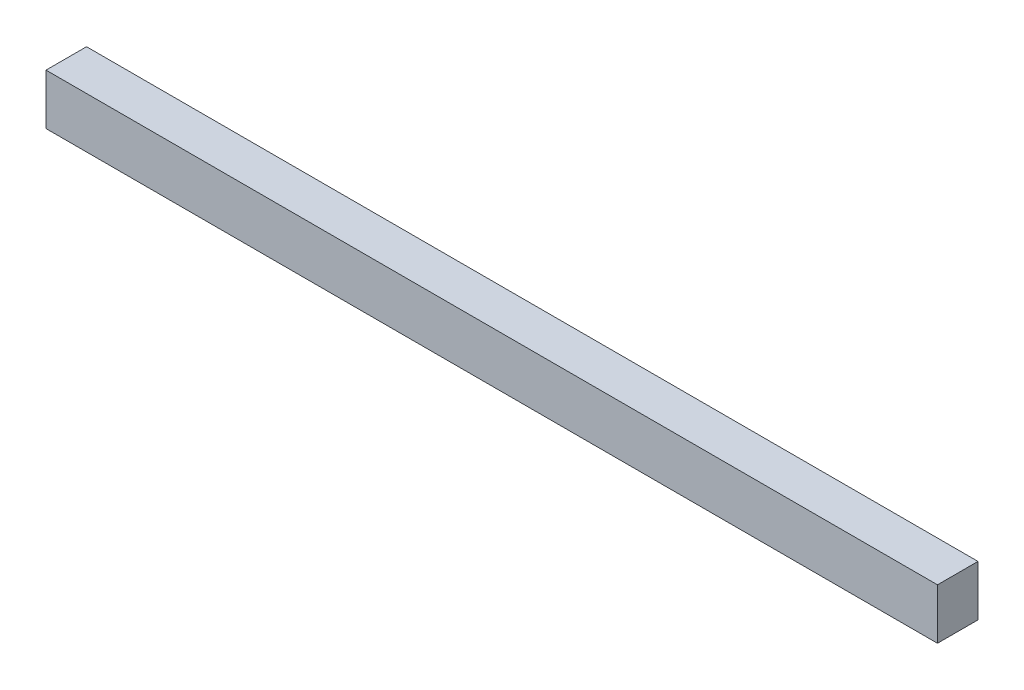
SolidWorks part; units mm, degrees
ref_plane "Front Plane" through (0, 0, 0) normal (0, 0, 1) x (1, 0, 0)
ref_plane "Top Plane" through (0, 0, 0) normal (0, 1, 0) x (1, 0, 0)
ref_plane "Right Plane" through (0, 0, 0) normal (1, 0, 0) x (0, 0, -1)
sketch "Sketch1" plane through (0, 0, 0) normal (0, 1, 0) x (1, 0, 0)
  line L1 (-220, 10) -> (220, 10)
  line L2 (-220, 10) -> (-220, -10)
  line L3 (-220, -10) -> (220, -10)
  line L4 (220, 10) -> (220, -10)
  line L5 (-220, 10) -> (220, -10) construction
  line L6 (-220, -10) -> (220, 10) construction
  point P0 (0, 0)
  dimension "D1" = 440
  dimension "D2" = 20
extrude "Boss-Extrude1" add sketch "Sketch1" along normal blind 25
hole_wizard "M5 Tapped Hole1" positions "Sketch4" profile "Sketch3" tap size "M5" standard "ISO"
sketch "Sketch4" plane through (0, 0, -10) normal (0, 0, -1) x (-1, 0, 0)
  line L0 (0, 0) -> (0, 25) construction
  line L1 (-220, 25) -> (220, 25) construction
  point P0 (0, 12.5)
  point P11 (0, 12.5)
  point P17 (60, 12.5)
  point P18 (120, 12.5)
  point P19 (180, 12.5)
  point P24 (-60, 12.5)
  point P25 (-120, 12.5)
  point P26 (-180, 12.5)
  dimension "D1" = 4
  dimension "D2" = 4
sketch "Sketch3" plane through (0, 12.5, -10) normal (1, 0, 0) x (0, 1, 0)
  line L0 (0, 0) -> (0, 16.2618)
  line L1 (0, 16.2618) -> (2.1, 15)
  line L2 (2.1, 15) -> (2.1, 0)
  line L5 (2.1, 0) -> (0, 0)
  line L10 (0, 16.2618) -> (-2.1, 15) construction
  line L11 (0, -6.35) -> (0, 107.95) construction
  dimension "Tap Drill Dia." = 4.2
  dimension "Tap Drill Depth" = 15
  dimension "Drill Angle" = 118
cosmetic thread "Hole Thread1" parameters "D1"=10, "D2"=5
cosmetic thread "Hole Thread2" parameters "D1"=10, "D2"=5
cosmetic thread "Hole Thread3" parameters "D1"=10, "D2"=5
cosmetic thread "Hole Thread4" parameters "D1"=10, "D2"=5
cosmetic thread "Hole Thread5" parameters "D1"=10, "D2"=5
cosmetic thread "Hole Thread6" parameters "D1"=10, "D2"=5
cosmetic thread "Hole Thread7" parameters "D1"=10, "D2"=5
